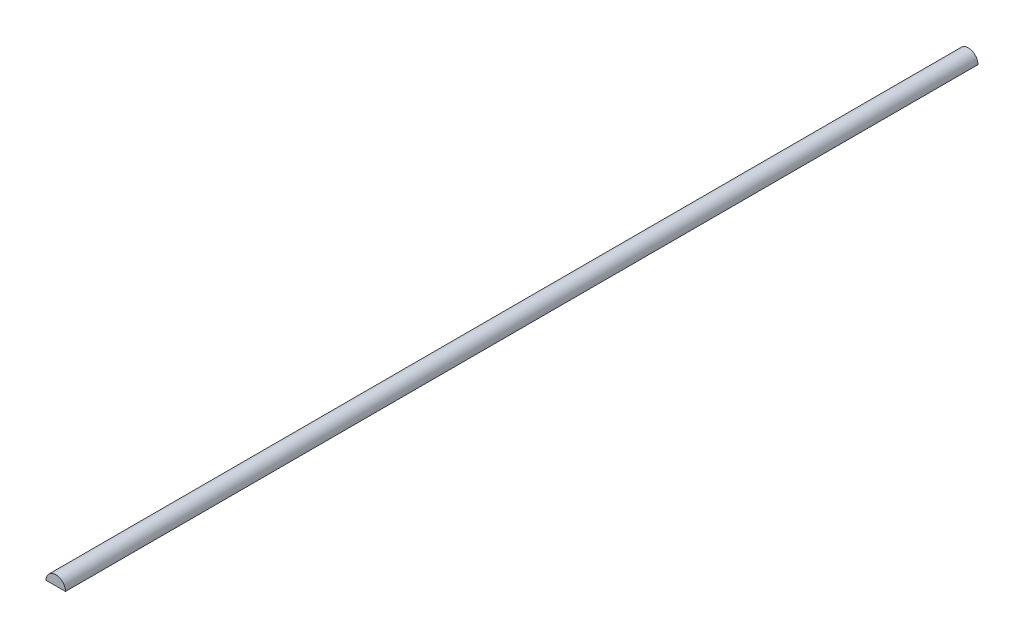
SolidWorks part; units mm, degrees
material "Custom Plastic"
ref_plane "Front Plane" through (0, 0, 0) normal (0, 0, 1) x (1, 0, 0)
ref_plane "Top Plane" through (0, 0, 0) normal (0, 1, 0) x (1, 0, 0)
ref_plane "Right Plane" through (0, 0, 0) normal (1, 0, 0) x (0, 0, -1)
sketch "Sketch1" plane through (0, 0, 0) normal (0, 0, 1) x (1, 0, 0)
  line L0 (0, 0) -> (4.05, 0)
  line L1 (0, 0) -> (-4.05, 0)
  arc A0 (4.05, 0) -> (-4.05, 0) centre (0, 0) ccw
  dimension "D1" = 8.1
extrude "Boss-Extrude1" add sketch "Sketch1" along normal blind 380
